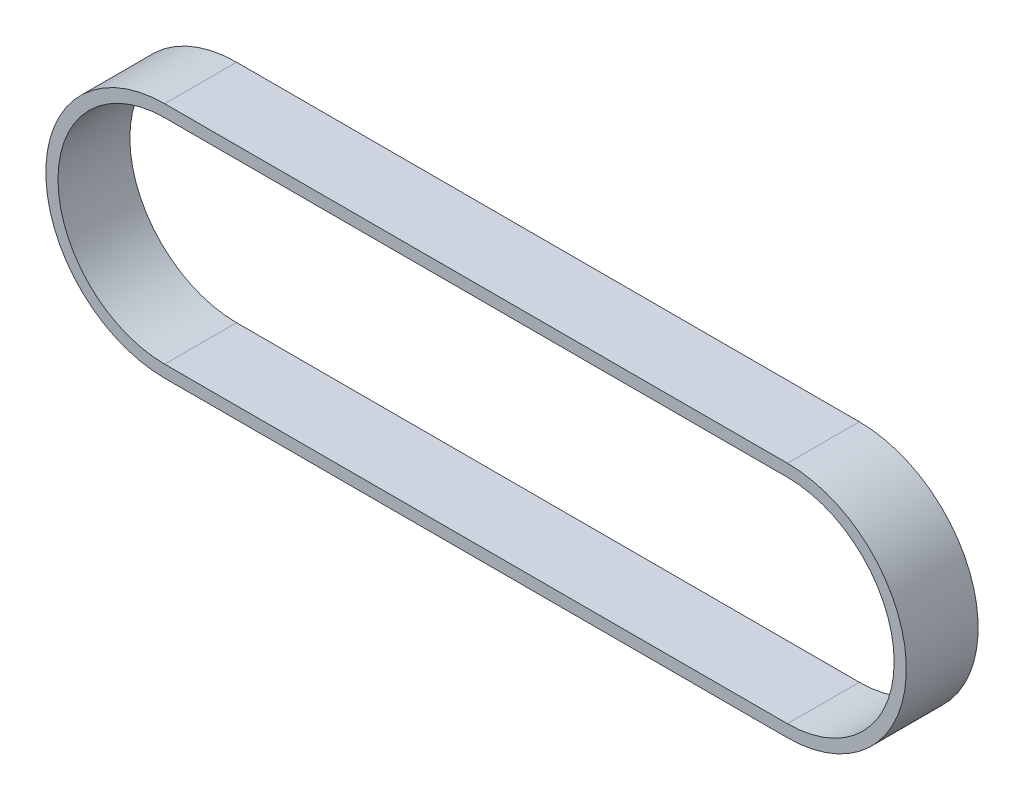
SolidWorks part; units mm, degrees
ref_plane "Front Plane" through (0, 0, 0) normal (0, 0, 1) x (1, 0, 0)
ref_plane "Top Plane" through (0, 0, 0) normal (0, 1, 0) x (1, 0, 0)
ref_plane "Right Plane" through (0, 0, 0) normal (1, 0, 0) x (0, 0, -1)
sketch "Sketch1" plane through (0, 0, 0) normal (0, 0, 1) x (1, 0, 0)
  line L0 (129.9972, 0) -> (0, 0) construction
  line L1 (0, 22.2758) -> (129.9972, 22.2758)
  line L2 (129.9972, -22.2758) -> (0, -22.2758)
  line L3 (64.9986, 22.2758) -> (64.9986, 2.5582) construction
  line L4 (0, 24.8158) -> (129.9972, 24.8158)
  line L5 (129.9972, -24.8158) -> (0, -24.8158)
  circle A0 centre (0, 0) radius 22.2758 construction
  circle A1 centre (129.9972, 0) radius 22.2758 construction
  arc A2 (0, -22.2758) -> (0, 22.2758) centre (0, 0) cw
  arc A3 (129.9972, -22.2758) -> (129.9972, 22.2758) centre (129.9972, 0) ccw
  arc A4 (129.9972, -24.8158) -> (129.9972, 24.8158) centre (129.9972, 0) ccw
  arc A5 (0, -24.8158) -> (0, 24.8158) centre (0, 0) cw
  dimension "D1" = 44.5516
  dimension "D2" = 129.9972
  dimension "D3" = 2.54
extrude "Boss-Extrude1" add sketch "Sketch1" along normal blind 15
